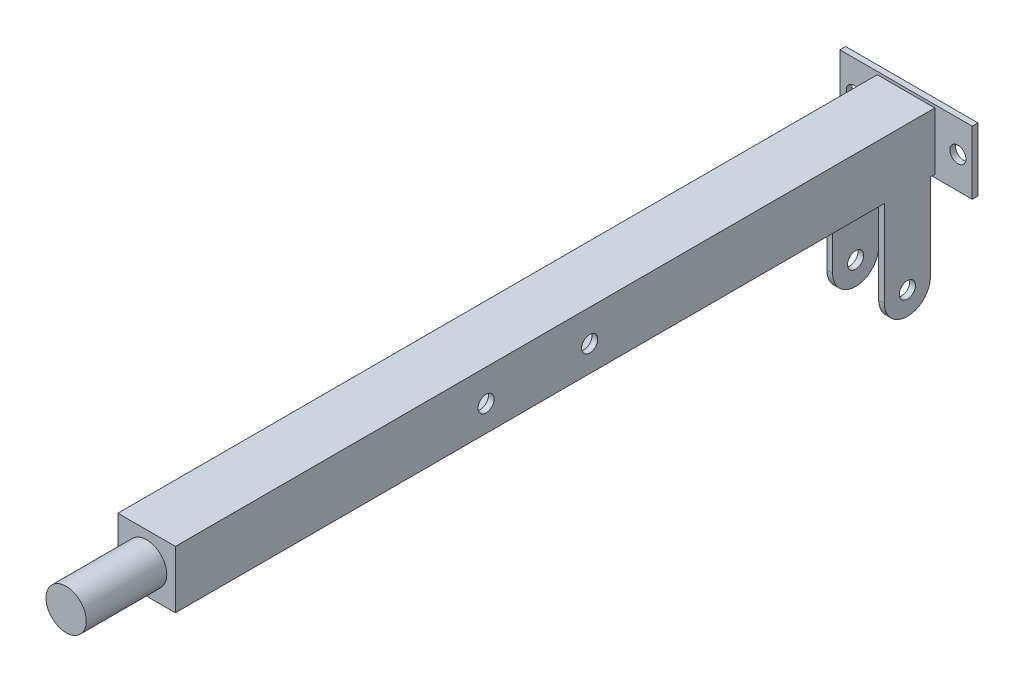
SolidWorks part; units mm, degrees
ref_plane "Front Plane" through (0, 0, 0) normal (0, 0, 1) x (1, 0, 0)
ref_plane "Top Plane" through (0, 0, 0) normal (0, 1, 0) x (1, 0, 0)
ref_plane "Right Plane" through (0, 0, 0) normal (1, 0, 0) x (0, 0, -1)
sketch "Sketch1" plane through (0, 0, 0) normal (0, 0, 1) x (1, 0, 0)
  line L0 (-90.5892, 0) -> (-52.0608, 0) construction
  line L8 (158.7805, 0) -> (4438.8721, 0) construction
  circle A0 centre (0, 0) radius 17.5
  dimension "D1" = 35
extrude "Boss-Extrude1" add sketch "Sketch1" along normal blind 70
sketch "Sketch3" plane through (0, 0, 0) normal (0, 1, 0) x (1, 0, 0)
  line L0 (0, 0) -> (0, 660)
  dimension "D1" = 660
sketch "Sketch4" plane through (0, 0, 0) normal (0, 0, -1) x (-1, 0, 0)
  line L1 (25, -25) -> (-25, -25)
  line L2 (25, -25) -> (25, 25)
  line L3 (25, 25) -> (-25, 25)
  line L4 (-25, -25) -> (-25, 25)
  line L5 (25, -25) -> (-25, 25) construction
  line L6 (25, 25) -> (-25, -25) construction
  point P0 (0, 0)
  dimension "D1" = 50
  dimension "D2" = 50
sweep "Sweep1" add profiles "Sketch4" path "Sketch3"
sketch "Sketch5" plane through (0, 0, -660) normal (0, 0, -1) x (-1, 0, 0)
  line L0 (-20, 20) -> (-20, -20)
  line L1 (-20, -20) -> (20, -20)
  line L2 (20, -20) -> (20, 20)
  line L3 (20, 20) -> (-20, 20)
  line L4 (-25, 25) -> (-25, -25)
  line L5 (-25, -25) -> (25, -25)
  line L6 (25, -25) -> (25, 25)
  line L7 (25, 25) -> (-25, 25)
  line L8 (-25, 25) -> (-25, -25)
  line L9 (-25, -25) -> (25, -25)
  line L10 (25, -25) -> (25, 25)
  line L11 (25, 25) -> (-25, 25)
  dimension "D1" = 0
  dimension "D2" = 5
extrude "Cut-Extrude1" cut sketch "Sketch5" against normal blind 650 and the other way through all contours L0 L1 L2 L3
sketch "Sketch6" plane through (0, 0, -660) normal (0, 0, -1) x (-1, 0, 0)
  line L0 (45, 0) -> (-45, 0) construction
  line L1 (57.5, -27.5) -> (-57.5, -27.5)
  line L2 (57.5, -27.5) -> (57.5, 27.5)
  line L3 (57.5, 27.5) -> (-57.5, 27.5)
  line L4 (-57.5, -27.5) -> (-57.5, 27.5)
  line L5 (57.5, -27.5) -> (-57.5, 27.5) construction
  line L6 (57.5, 27.5) -> (-57.5, -27.5) construction
  circle A0 centre (-45, 0) radius 7
  circle A1 centre (45, 0) radius 7
  point P0 (0, 0)
  point P9 (0, 0)
  dimension "D3" = 14
  dimension "D1" = 55
  dimension "D2" = 115
extrude "Boss-Extrude2" add sketch "Sketch6" along normal blind 5
sketch "Sketch8" plane through (0, -25, 0) normal (0, -1, 0) x (1, 0, 0)
  line L1 (25, -660) -> (25, -620)
  line L3 (25, 0) -> (25, -660) construction
  line L4 (20, -660) -> (20, -620)
  line L5 (20, -620) -> (25, -620)
  line L6 (20, -660) -> (25, -660)
  line L7 (0, 0) -> (0, -660) construction
  line L8 (0, 0) -> (0, -660)
  line L9 (-20, -660) -> (-20, -620)
  line L10 (-20, -620) -> (-25, -620)
  line L11 (-25, -660) -> (-25, -620)
  line L12 (-20, -660) -> (-25, -660)
  point P2 (0, -640)
  point P8 (25, -640)
  dimension "D1" = 20
  dimension "D2" = 5
sketch "Sketch11" plane through (-25, 0, 0) normal (-1, 0, 0) x (0, 0, 1)
  line L0 (-660, -25) -> (-620, -25) construction
  line L1 (-660, -25) -> (-620, -25)
  line L2 (-660, -25) -> (-620, -25) construction
  line L3 (-660, -25) -> (-620, -25)
sketch "Sketch12" plane through (-25, 0, 0) normal (-1, 0, 0) x (0, 0, 1)
  line L0 (-656.1404, -25) -> (-616.1404, -25)
  line L1 (-660, -25) -> (-620, -25) construction
  line L2 (0, -25) -> (-660, -25) construction
  line L4 (-656.1404, -25) -> (-616.1404, -25)
  line L5 (-656.1404, -25) -> (-656.1404, -100)
  line L7 (-616.1404, -25) -> (-616.1404, -100)
  arc A0 (-656.1404, -100) -> (-616.1404, -100) centre (-636.1404, -100) ccw
  line M8 (-660, -25) -> (0, -25)
  dimension "D3" = 20
  dimension "D1" = 40
  dimension "D2" = 75
extrude "Boss-Extrude4" add sketch "Sketch12" against normal blind 5 contours L5 A0 L7 M8
sketch "Sketch13" plane through (-25, 0, 0) normal (-1, 0, 0) x (0, 0, 1)
  circle A0 centre (-636.1404, -100) radius 7
  dimension "D1" = 14
extrude "Cut-Extrude4" cut sketch "Sketch13" against normal through all
mirror "Mirror1" about plane through (0, 0, 0) normal (1, 0, 0) of "Boss-Extrude4"
mirror "Mirror2" about plane through (0, 0, 0) normal (1, 0, 0) of "Cut-Extrude4"
sketch "Sketch14" plane through (25, 0, 0) normal (1, 0, 0) x (0, 0, -1)
  circle A0 centre (270, -2.5) radius 7
  circle A1 centre (360, -2.5) radius 7
extrude "Cut-Extrude5" cut sketch "Sketch14" against normal through all both and the other way through all
